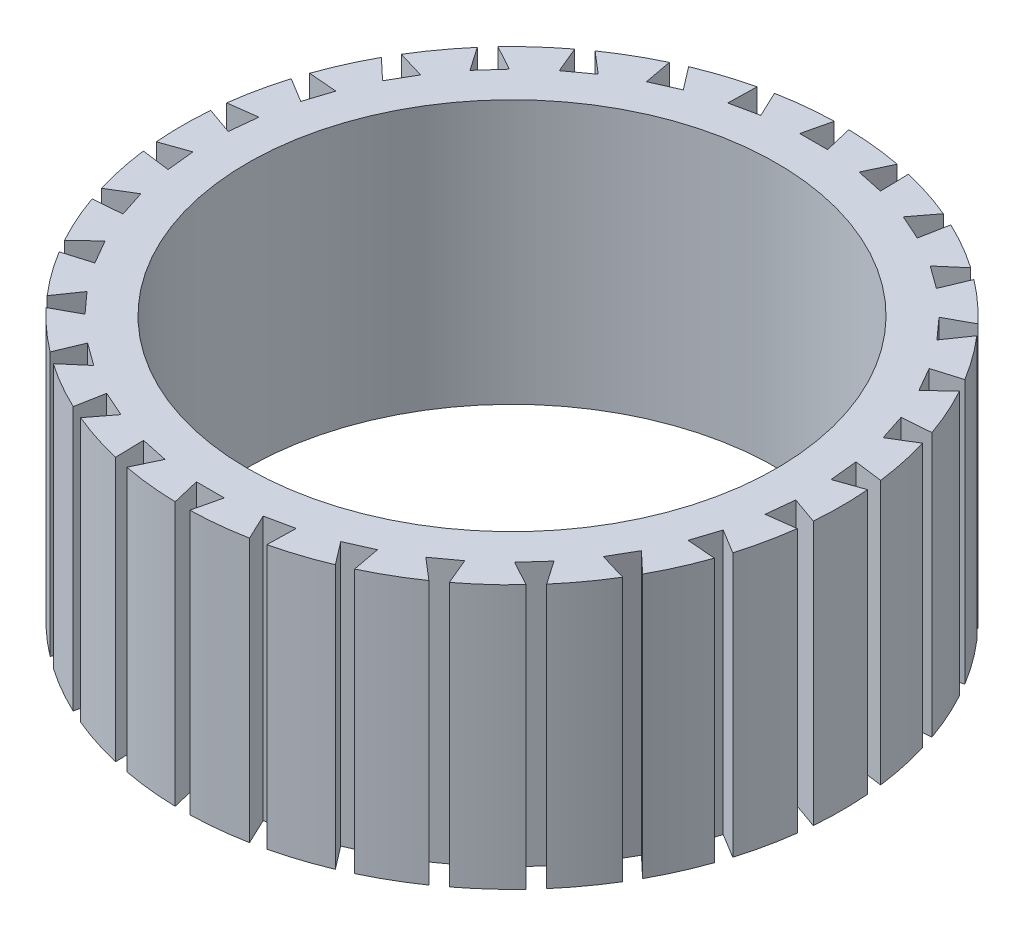
SolidWorks part; units mm, degrees
ref_plane "Front Plane" through (0, 0, 0) normal (0, 0, 1) x (1, 0, 0)
ref_plane "Top Plane" through (0, 0, 0) normal (0, 1, 0) x (1, 0, 0)
ref_plane "Right Plane" through (0, 0, 0) normal (1, 0, 0) x (0, 0, -1)
sketch "Sketch1" plane through (0, 0, 0) normal (0, 1, 0) x (1, 0, 0)
  circle A0 centre (0, 0) radius 16.2
  circle A1 centre (0, 0) radius 13
  dimension "D1" = 3.2
  dimension "D2" = 26
extrude "Boss-Extrude1" add sketch "Sketch1" along normal blind 12.9635
sketch "Sketch2" plane through (0, 0, 0) normal (0, 1, 0) x (1, 0, 0)
  line L0 (0, 16.2) -> (0, 0) construction
  line L1 (0.6847, 14.8247) -> (-0.6847, 14.8247)
  line L2 (-0.6847, 14.8247) -> (-0.359, 16.196)
  line L3 (-0.359, 16.196) -> (-0.359, 18.0528)
  line L4 (-0.359, 18.0528) -> (0.359, 18.0528)
  line L5 (0.359, 16.196) -> (0.359, 18.0528)
  line L6 (0.6847, 14.8247) -> (0.359, 16.196)
  circle A0 centre (0, 0) radius 16.2 construction
  point P11 (0, 18.0528)
  point P13 (0, 14.8247)
extrude "Cut-Extrude1" cut sketch "Sketch2" along normal through all
pattern_circular "CirPattern1" count 30 over 360 about axis through (0, 0, 0) along (0, 1, 0) of "Cut-Extrude1"
